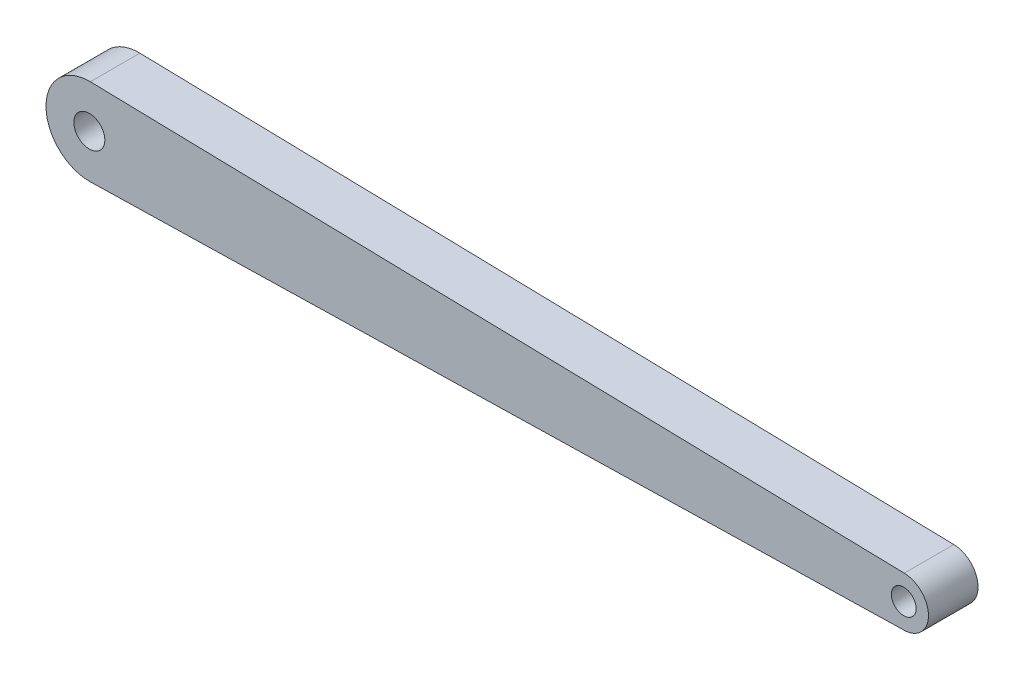
SolidWorks part; units mm, degrees
ref_plane "Front Plane" through (0, 0, 0) normal (0, 0, 1) x (1, 0, 0)
ref_plane "Top Plane" through (0, 0, 0) normal (0, 1, 0) x (1, 0, 0)
ref_plane "Right Plane" through (0, 0, 0) normal (1, 0, 0) x (0, 0, -1)
sketch "Sketch1" plane through (0, 0, 0) normal (0, 0, 1) x (1, 0, 0)
  line L0 (-1313.403, 69.9818) -> (0.9125, 39.9896)
  line L1 (-1313.403, -69.9818) -> (0.9125, -39.9896)
  circle A0 centre (0, 0) radius 20
  circle A1 centre (-1315, 0) radius 25
  arc A2 (-1313.403, 69.9818) -> (-1313.403, -69.9818) centre (-1315, 0) ccw
  arc A3 (0.9125, 39.9896) -> (0.9125, -39.9896) centre (0, 0) cw
  point P9 (0, 0)
  point P10 (0, 0)
  dimension "D1" = 50
  dimension "D2" = 40
  dimension "D3" = 70
  dimension "D4" = 40
  dimension "D5" = 1315
extrude "Boss-Extrude1" add sketch "Sketch1" along normal mid plane 80
